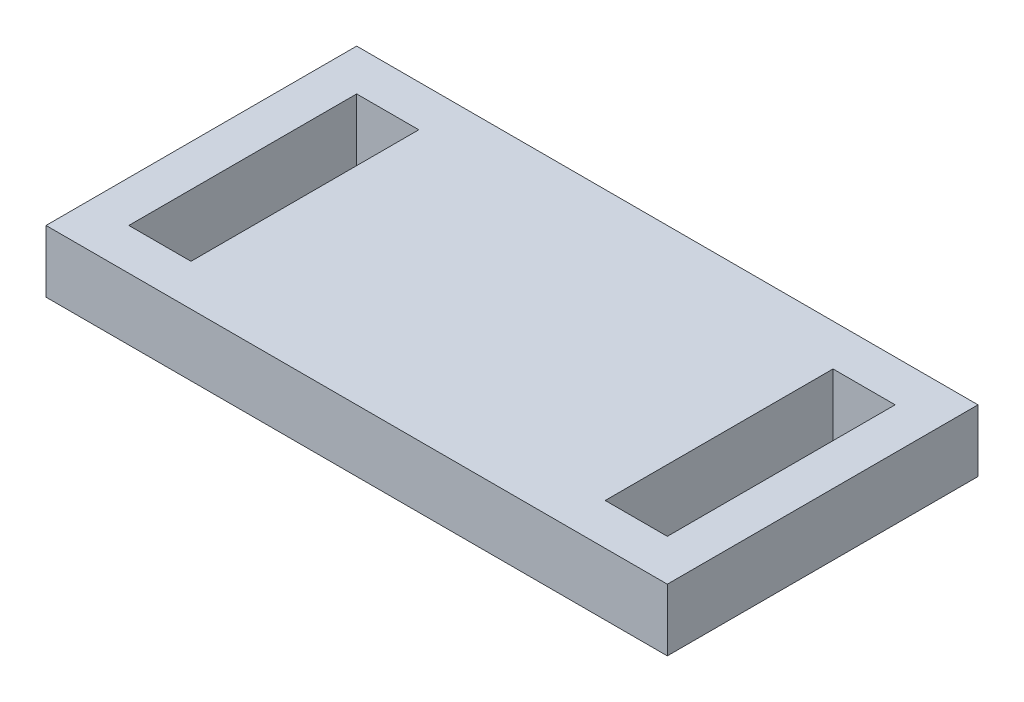
SolidWorks part; units mm, degrees
material "Acrylic (Medium-high impact)"
ref_plane "Front Plane" through (0, 0, 0) normal (0, 0, 1) x (1, 0, 0)
ref_plane "Top Plane" through (0, 0, 0) normal (0, 1, 0) x (1, 0, 0)
ref_plane "Right Plane" through (0, 0, 0) normal (1, 0, 0) x (0, 0, -1)
sketch "Sketch1" plane through (0, 0, 0) normal (0, 1, 0) x (1, 0, 0)
  line L1 (-15, 7.5) -> (15, 7.5)
  line L2 (-15, 7.5) -> (-15, -7.5)
  line L3 (-15, -7.5) -> (15, -7.5)
  line L4 (15, 7.5) -> (15, -7.5)
  line L5 (-15, 7.5) -> (15, -7.5) construction
  line L6 (-15, -7.5) -> (15, 7.5) construction
  point P0 (0, 0)
  dimension "D1" = 30
  dimension "D2" = 15
extrude "MainPlate" add sketch "Sketch1" along normal blind 3
sketch "Sketch3" plane through (0, 3, 0) normal (0, 1, 0) x (1, 0, 0)
  line L0 (10, 5.5) -> (13, 5.5)
  line L1 (-13, 5.5) -> (-10, 5.5)
  line L2 (-13, 5.5) -> (-13, -5.5)
  line L3 (-13, -5.5) -> (-10, -5.5)
  line L4 (-10, 5.5) -> (-10, -5.5)
  line L5 (10, 5.5) -> (10, -5.5)
  line L6 (10, -5.5) -> (13, -5.5)
  line L7 (13, 5.5) -> (13, -5.5)
  dimension "D1" = 10
  dimension "D2" = 3
  dimension "D3" = 11
  dimension "D4" = 5.5
  dimension "D6" = 10
  dimension "D7" = 5.5
  dimension "D5" = 2
extrude "TabHoles" cut sketch "Sketch3" against normal through all
sketch "Sketch5" plane through (0, 0, 0) normal (0, 1, 0) x (1, 0, 0)
  line L14 (-15.1442, -7.6442) -> (15.1442, -7.6442)
  line L15 (15.1442, -7.6442) -> (15.1442, 7.6442)
  line L16 (15.1442, 7.6442) -> (-15.1442, 7.6442)
  line L17 (-15.1442, 7.6442) -> (-15.1442, -7.6442)
  line L18 (-15.1442, -7.6442) -> (15.1442, -7.6442)
  line L19 (15.1442, -7.6442) -> (15.1442, 7.6442)
  line L20 (15.1442, 7.6442) -> (-15.1442, 7.6442)
  line L21 (-15.1442, 7.6442) -> (-15.1442, -7.6442)
  line L33 (-12.8558, -5.3558) -> (-10.1442, -5.3558)
  line L34 (-10.1442, -5.3558) -> (-10.1442, 5.3558)
  line L35 (-10.1442, 5.3558) -> (-12.8558, 5.3558)
  line L36 (-12.8558, 5.3558) -> (-12.8558, -5.3558)
  line L37 (-12.8558, -5.3558) -> (-10.1442, -5.3558)
  line L38 (-10.1442, -5.3558) -> (-10.1442, 5.3558)
  line L39 (-10.1442, 5.3558) -> (-12.8558, 5.3558)
  line L40 (-12.8558, 5.3558) -> (-12.8558, -5.3558)
  line L51 (10.1442, -5.3558) -> (12.8558, -5.3558)
  line L52 (12.8558, -5.3558) -> (12.8558, 5.3558)
  line L53 (12.8558, 5.3558) -> (10.1442, 5.3558)
  line L54 (10.1442, 5.3558) -> (10.1442, -5.3558)
  line L55 (10.1442, -5.3558) -> (12.8558, -5.3558)
  line L56 (12.8558, -5.3558) -> (12.8558, 5.3558)
  line L57 (12.8558, 5.3558) -> (10.1442, 5.3558)
  line L58 (10.1442, 5.3558) -> (10.1442, -5.3558)
  dimension "D1" = 0.1442
  dimension "D2" = 0.1442
  dimension "D3" = 0.1442
extrude "FOR THE LASER CUTTER" [suppressed] add sketch "Sketch5" along normal blind 3
equation "\"D6@Sketch3\"=\"D1@Sketch3\""
equation "\"D7@Sketch3\"=\"D4@Sketch3\""
